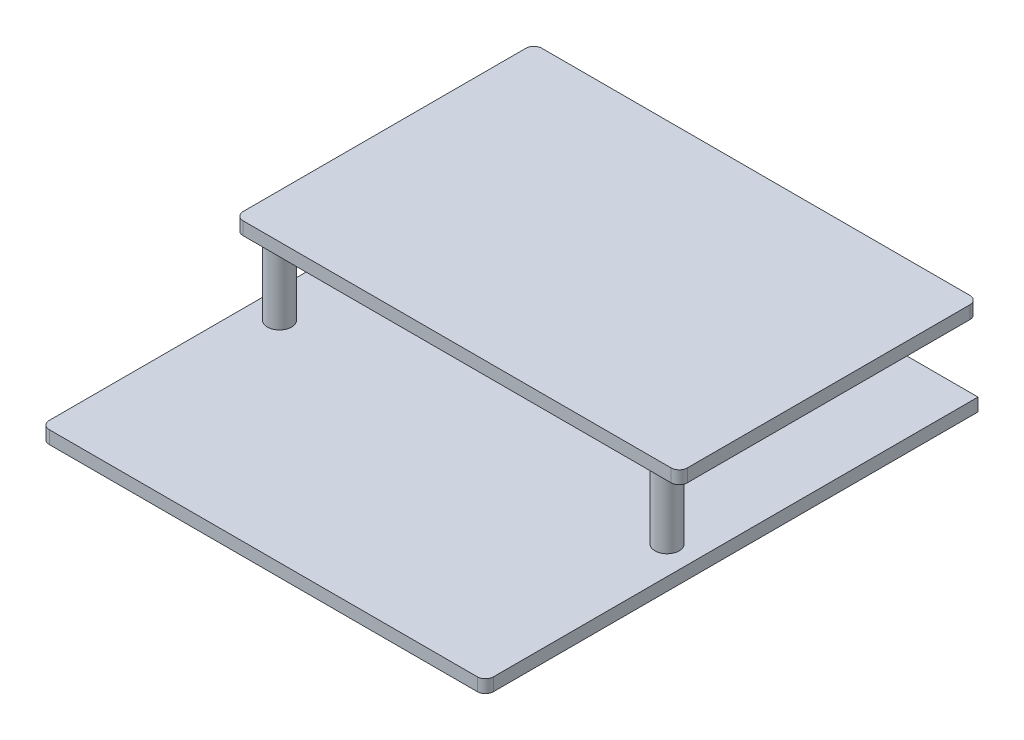
SolidWorks part; units mm, degrees
ref_plane "Front Plane" through (0, 0, 0) normal (0, 0, 1) x (1, 0, 0)
ref_plane "Top Plane" through (0, 0, 0) normal (0, 1, 0) x (1, 0, 0)
ref_plane "Right Plane" through (0, 0, 0) normal (1, 0, 0) x (0, 0, -1)
sketch "Sketch1" plane through (0, 0, 0) normal (0, 1, 0) x (1, 0, 0)
  line L1 (27.5, -30.5) -> (-27.5, -30.5)
  line L2 (27.5, -30.5) -> (27.5, 30.5)
  line L3 (27.5, 30.5) -> (-27.5, 30.5)
  line L4 (-27.5, -30.5) -> (-27.5, 30.5)
  line L5 (27.5, -30.5) -> (-27.5, 30.5) construction
  line L6 (27.5, 30.5) -> (-27.5, -30.5) construction
  point P0 (0, 0)
  dimension "D1" = 55
  dimension "D2" = 61
extrude "Boss-Extrude1" add sketch "Sketch1" along normal blind 1.6
sketch "Sketch2" plane through (0, 1.6, 0) normal (0, 1, 0) x (1, 0, 0)
  line L0 (27.5, 30.5) -> (-27.5, 30.5) construction
  line L1 (-27.5, 30.5) -> (-27.5, -30.5) construction
  line L2 (27.5, -30.5) -> (27.5, 30.5) construction
  circle A0 centre (-24, -4.5) radius 1.5
  circle A1 centre (24, -4.5) radius 1.5
  dimension "D2" = 3
  dimension "D3" = 3.5
  dimension "D4" = 3.5
  dimension "D1" = 35
extrude "Boss-Extrude2" add sketch "Sketch2" along normal blind 8.8
sketch "Sketch3" plane through (0, 10.4, 0) normal (0, 1, 0) x (1, 0, 0)
  line L0 (-27.5, 30.5) -> (-27.5, -30.5) construction
  line L1 (27.5, -6.5) -> (-27.5, -6.5)
  line L2 (27.5, -6.5) -> (27.5, 30.5)
  line L3 (27.5, 30.5) -> (-27.5, 30.5)
  line L4 (-27.5, -6.5) -> (-27.5, 30.5)
  line L5 (27.5, -6.5) -> (-27.5, 30.5) construction
  line L6 (27.5, 30.5) -> (-27.5, -6.5) construction
  line L7 (27.5, 30.5) -> (-27.5, 30.5) construction
  line L8 (27.5, -30.5) -> (27.5, 30.5) construction
  point P0 (0, 12)
  dimension "D1" = 37
extrude "Boss-Extrude3" add sketch "Sketch3" along normal blind 1.6
fillet "Fillet1" radius 1 7 edges at (27.5, 0.8, 30.5) (-27.5, 0.8, 30.5) (27.5, 11.2, -30.5) (27.5, 11.2, 6.5) (-27.5, 0.8, -30.5) (-27.5, 11.2, -30.5) (-27.5, 11.2, 6.5)
